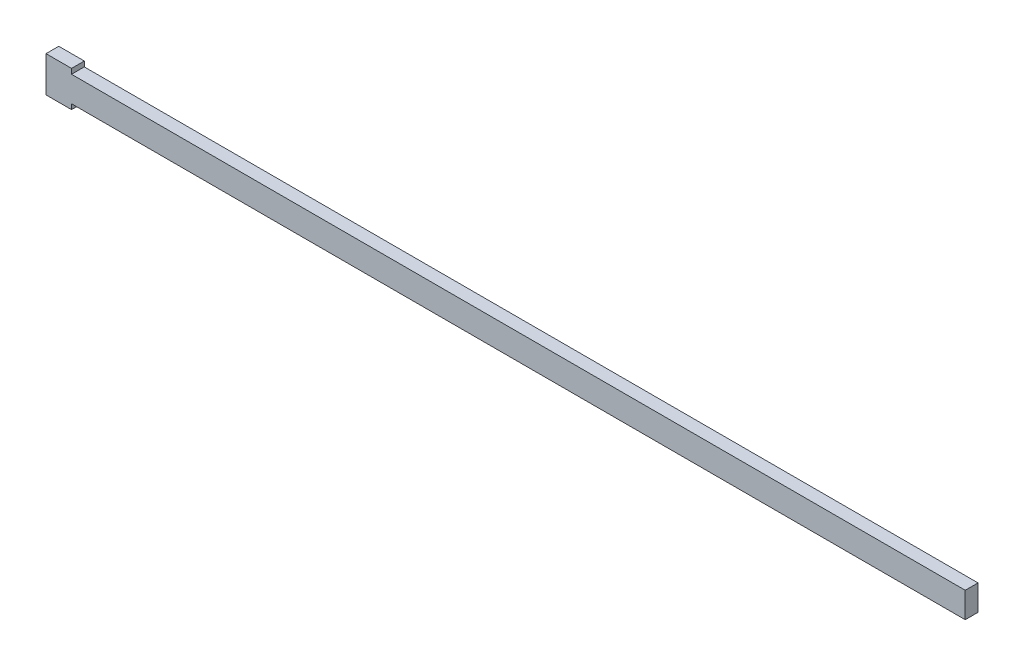
SolidWorks part; units mm, degrees
ref_plane "Front Plane" through (0, 0, 0) normal (0, 0, 1) x (1, 0, 0)
ref_plane "Top Plane" through (0, 0, 0) normal (0, 1, 0) x (1, 0, 0)
ref_plane "Right Plane" through (0, 0, 0) normal (1, 0, 0) x (0, 0, -1)
sketch "Sketch1" plane through (0, 0, 0) normal (0, 0, 1) x (1, 0, 0)
  line L0 (0, 6.35) -> (34.4054, 6.35) construction
  line L1 (12.7, 0) -> (457.2, 0)
  line L2 (0, 0) -> (0, 12.7)
  line L3 (12.7, 12.7) -> (457.2, 12.7)
  line L4 (457.2, 0) -> (457.2, 12.7)
  line L6 (0, 12.7) -> (0, 15.24)
  line L7 (0, 15.24) -> (12.7, 15.24)
  line L8 (12.7, 12.7) -> (12.7, 15.24)
  line L9 (12.7, 0) -> (12.7, -2.54)
  line L10 (0, -2.54) -> (12.7, -2.54)
  line L11 (0, -2.54) -> (0, 0)
  dimension "D1" = 12.7
  dimension "D2" = 457.2
  dimension "D3" = 2.54
  dimension "D4" = 12.7
extrude "Boss-Extrude1" add sketch "Sketch1" along normal blind 6.35
